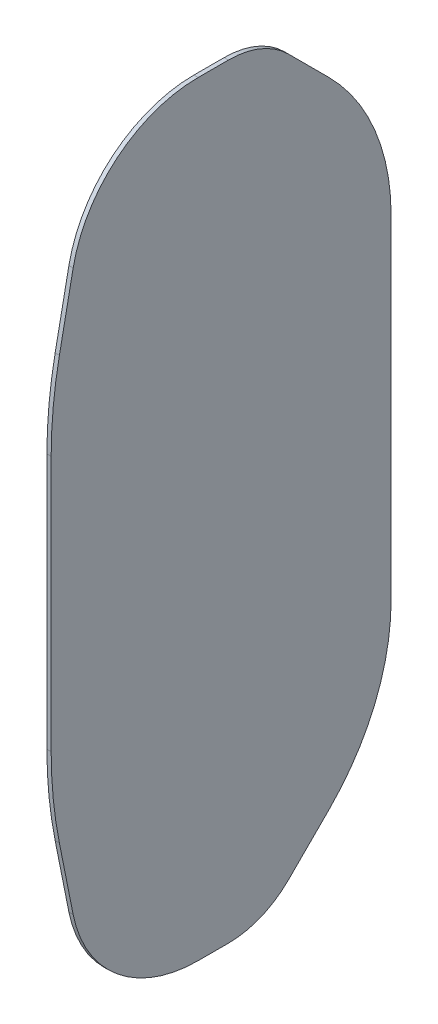
SolidWorks part; units mm, degrees
material "PC High Viscosity"
ref_plane "Front Plane" through (0, 0, 0) normal (1, 0, 0) x (0, 1, 0)
ref_plane "Top Plane" through (0, 0, 0) normal (0, 0, 1) x (0, 1, 0)
ref_plane "Right Plane" through (0, 0, 0) normal (0, 1, 0) x (-1, 0, 0)
sketch "Sketch1" plane through (0, 0, 0) normal (1, 0, 0) x (0, 1, 0)
  line L0 (-103.584, 0) -> (122.7047, 0) construction
  line L1 (0, 62.869) -> (0, -64.6539) construction
  line L3 (-40, 40) -> (40, 40)
  line L4 (-90, 40) -> (-90, -40) construction
  line L5 (-60, -40) -> (60, -40)
  line L6 (90, 40) -> (90, -40) construction
  line L8 (-90, 40) -> (-40, 40) construction
  line L11 (40, 40) -> (90, 40) construction
  line L12 (-90, -40) -> (-60, -40) construction
  line L13 (60, -40) -> (90, -40) construction
  line L14 (-90, -10) -> (-90, 0)
  line L15 (-90, 0) -> (-90, 30)
  line L16 (-90, 30) -> (-40, 40)
  line L17 (-90, -10) -> (-60, -40)
  line L18 (90, -10) -> (60, -40)
  line L19 (90, -10) -> (90, 0)
  line L20 (90, 0) -> (90, 30)
  line L21 (90, 30) -> (40, 40)
  point P10 (-90, 0)
  dimension "D1" = 180
  dimension "D2" = 80
  dimension "D3" = 120
  dimension "D4" = 10
  dimension "D5" = 80
  dimension "D6" = 90
  dimension "D7" = 30
extrude "Boss-Extrude1" add sketch "Sketch1" along normal blind 1
fillet "Fillet1" radius 100 2 edges at (0.5, 40, 40) (0.5, -40, 40)
fillet "Fillet2" radius 30 2 edges at (0.5, 90, 30) (0.5, -90, 30)
fillet "Fillet3" radius 20 2 edges at (0.5, -90, -10) (0.5, 90, -10)
fillet "Fillet4" radius 50 2 edges at (0.5, 60, -40) (0.5, -60, -40)
